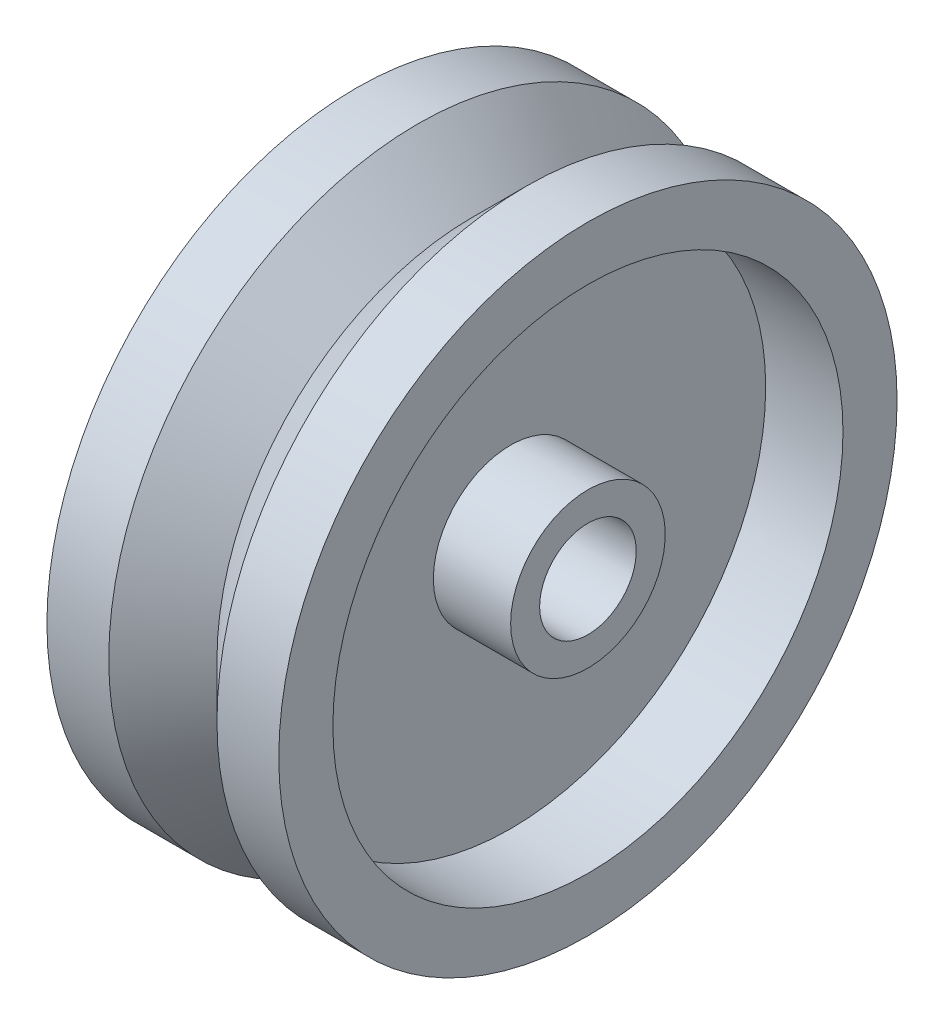
SolidWorks part; units mm, degrees
ref_plane "Front Plane" through (0, 0, 0) normal (0, 0, 1) x (1, 0, 0)
ref_plane "Top Plane" through (0, 0, 0) normal (0, 1, 0) x (1, 0, 0)
ref_plane "Right Plane" through (0, 0, 0) normal (1, 0, 0) x (0, 0, -1)
sketch "Sketch1" plane through (0, 0, 0) normal (0, 0, 1) x (1, 0, 0)
  line L0 (0, 0) -> (9977.8343, 0) construction
  line L1 (0, 0) -> (0, 9977.8343) construction
  line L2 (-7.5, 20) -> (-3.5, 20)
  line L3 (-3.5, 20) -> (0, 16.5)
  line L4 (0, 16.5) -> (3.5, 20)
  line L5 (3.5, 20) -> (7.5, 20)
  line L6 (-7.5, 20) -> (-7.5, 16.5)
  line L7 (-7.5, 16.5) -> (-2.5, 16.5)
  line L8 (-2.5, 16.5) -> (-2.5, 5)
  line L9 (-2.5, 5) -> (-7.5, 5)
  line L10 (-7.5, 5) -> (-7.5, 3.125)
  line L11 (-7.5, 3.125) -> (7.5, 3.125)
  line L12 (7.5, 5) -> (7.5, 3.125)
  line L13 (2.5, 5) -> (7.5, 5)
  line L14 (2.5, 16.5) -> (2.5, 5)
  line L15 (7.5, 16.5) -> (2.5, 16.5)
  line L16 (7.5, 20) -> (7.5, 16.5)
  dimension "D1" = 15
  dimension "D2" = 4
  dimension "D4" = 40
  dimension "D5" = 33
  dimension "D6" = 5
  dimension "D7" = 10
  dimension "D8" = 6.25
revolve "Revolve1" add sketch "Sketch1" angle 360 about L0
